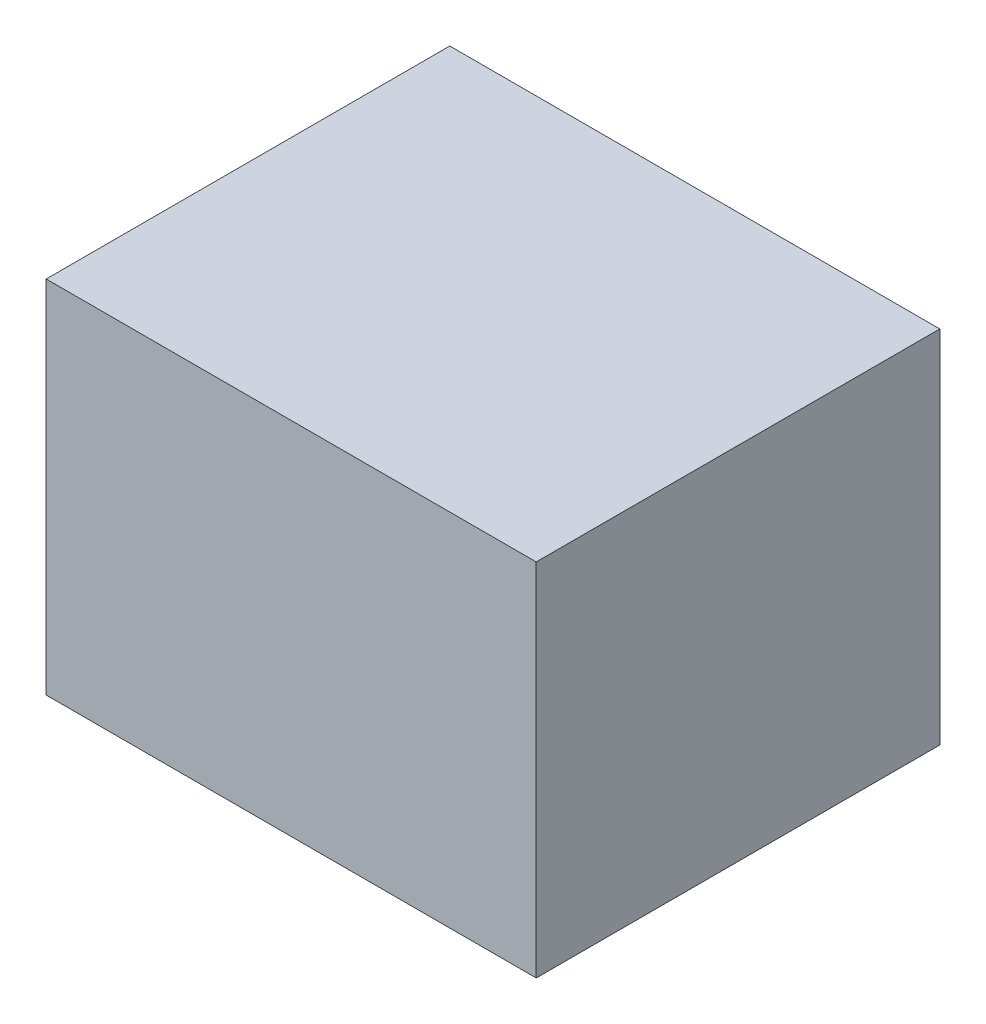
SolidWorks part; units mm, degrees
material "Balsa"
ref_plane "Front Plane" through (0, 0, 0) normal (0, 0, 1) x (1, 0, 0)
ref_plane "Top Plane" through (0, 0, 0) normal (0, 1, 0) x (1, 0, 0)
ref_plane "Right Plane" through (0, 0, 0) normal (1, 0, 0) x (0, 0, -1)
sketch "Sketch1" plane through (0, 0, 0) normal (0, 1, 0) x (1, 0, 0)
  line L1 (-170, 140) -> (170, 140)
  line L2 (-170, 140) -> (-170, -140)
  line L3 (-170, -140) -> (170, -140)
  line L4 (170, 140) -> (170, -140)
  line L5 (-170, 140) -> (170, -140) construction
  line L6 (-170, -140) -> (170, 140) construction
  point P0 (0, 0)
  dimension "D1" = 340
  dimension "D2" = 280
extrude "Boss-Extrude1" add sketch "Sketch1" along normal blind 250
